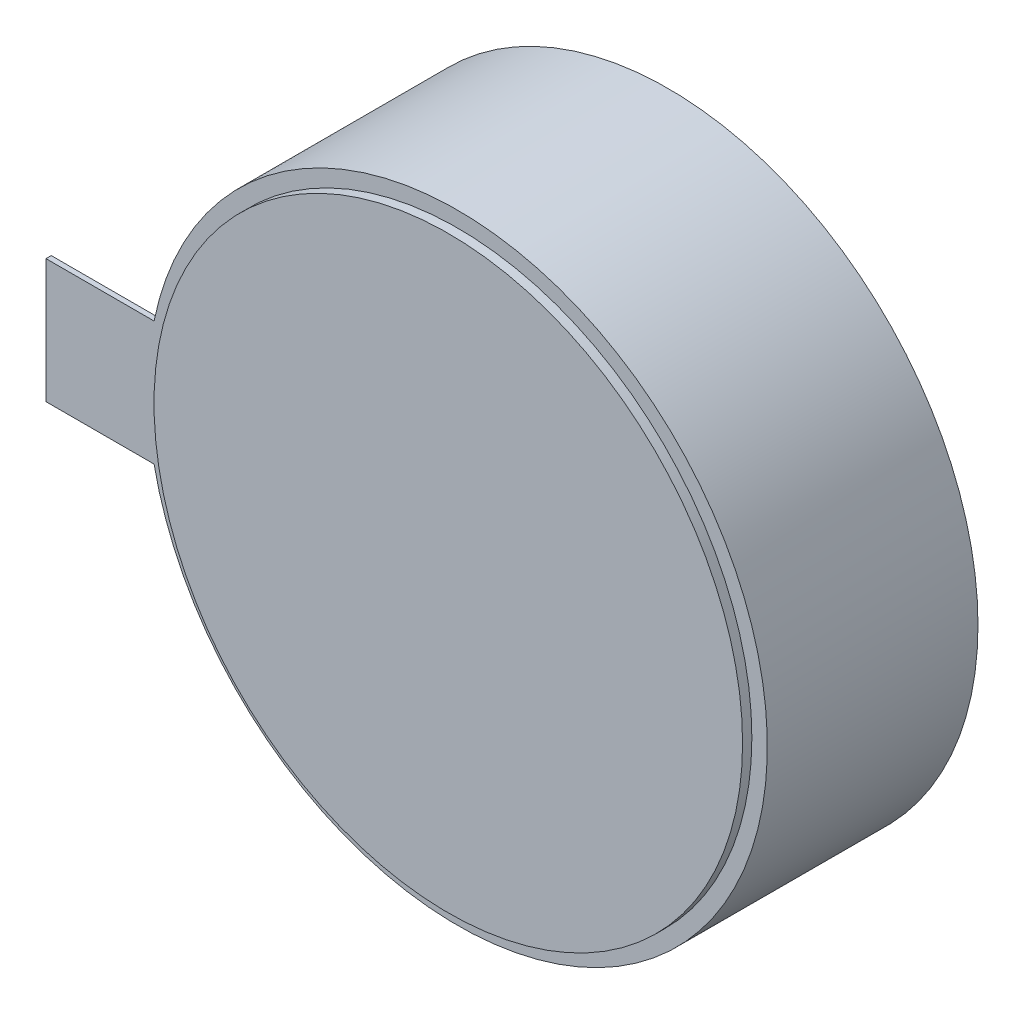
SolidWorks part; units mm, degrees
ref_plane "Front Plane" through (0, 0, 0) normal (0, 0, 1) x (1, 0, 0)
ref_plane "Top Plane" through (0, 0, 0) normal (0, 1, 0) x (1, 0, 0)
ref_plane "Right Plane" through (0, 0, 0) normal (1, 0, 0) x (0, 0, -1)
sketch "Sketch1" plane through (0, 0, 0) normal (0, 0, 1) x (1, 0, 0)
  circle A0 centre (0, 0) radius 5
  dimension "D1" = 10
extrude "Boss-Extrude1" add sketch "Sketch1" along normal blind 3.4 contours A0
sketch "Sketch2" plane through (0, 0, 3.4) normal (0, 0, 1) x (1, 0, 0)
  circle A0 centre (0, 0) radius 4.75
  dimension "D1" = 9.5
extrude "Boss-Extrude2" add sketch "Sketch2" along normal blind 0.15 contours A0
sketch "Sketch4" plane through (0, 0, 3.4) normal (0, 0, 1) x (1, 0, 0)
  line L0 (0, 0) -> (-11.1043, 0) construction
  line L1 (-4.6435, 1) -> (-6.6435, 1)
  line L3 (-4.6435, -1) -> (-6.6435, -1)
  line L4 (-6.6435, 1) -> (-6.6435, -1)
  circle A0 centre (0, 0) radius 4.75 construction
  circle A1 centre (0, 0) radius 4.75 construction
  arc A2 (-4.6435, 1) -> (-4.6435, -1) centre (0, 0) ccw
  point P9 (-6.6435, 0)
extrude "Boss-Extrude3" add sketch "Sketch4" against normal blind 0.085
sketch "Sketch7" plane through (0, 0, 3.315) normal (0, 0, -1) x (-1, 0, 0)
  line L0 (4.9776, 0.4733) -> (8.1477, 0.4733)
  line L2 (4.9859, -0.3758) -> (8.1313, -0.3758)
  circle A0 centre (0, 0) radius 5 construction
  arc A1 (4.899, -1) -> (4.899, 1) centre (0, 0) ccw construction
  point P6 (0, 0)
